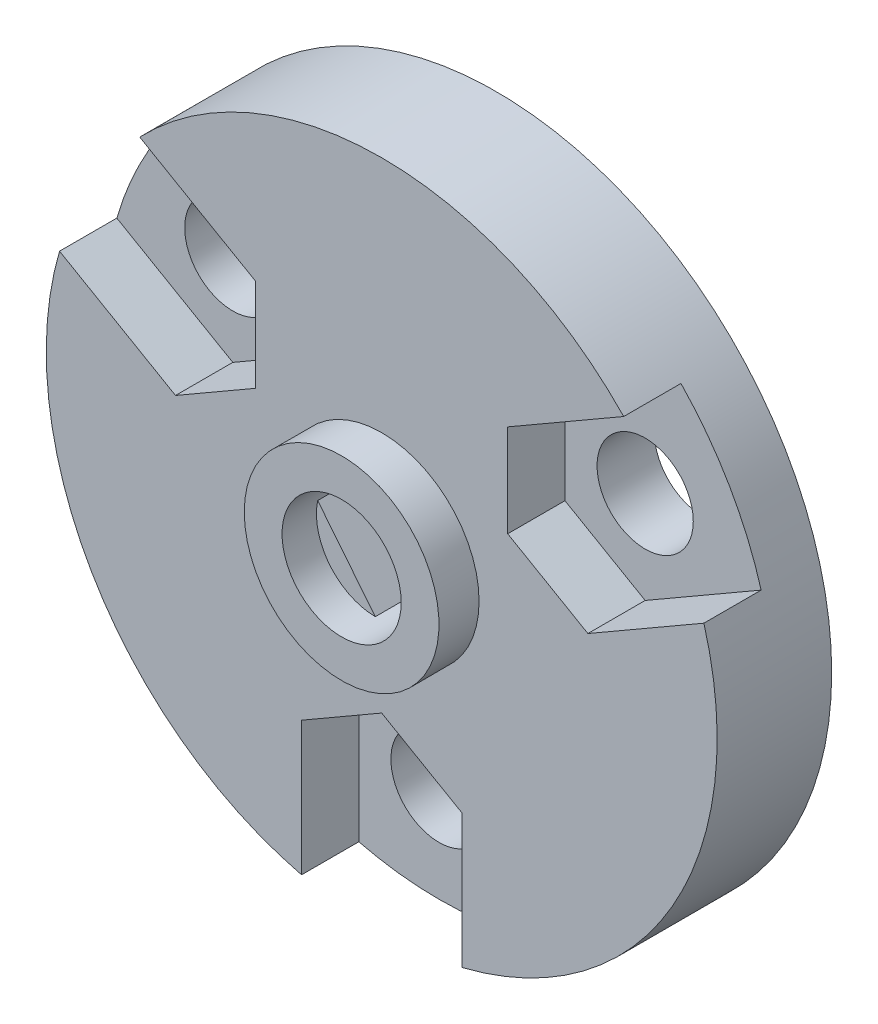
SolidWorks part; units mm, degrees
ref_plane "Front Plane" through (0, 0, 0) normal (0, 0, 1) x (1, 0, 0)
ref_plane "Top Plane" through (0, 0, 0) normal (0, 1, 0) x (1, 0, 0)
ref_plane "Right Plane" through (0, 0, 0) normal (1, 0, 0) x (0, 0, -1)
sketch "Sketch1" plane through (0, 0, 0) normal (0, 0, 1) x (1, 0, 0)
  circle A0 centre (0, 0) radius 14.6423
  circle A1 centre (0, 0) radius 14.6423 construction
extrude "Boss-Extrude1" add sketch "Sketch1" along normal blind 2.5
ref_plane "Plane1" through (0, 0, 2.5) normal (0, 0, 1) x (1, 0, 0)
sketch "Sketch2" plane through (0, 0, 2.5) normal (0, 0, 1) x (1, 0, 0)
  line L0 (9, 9.2376) -> (12.5, 7.2169) construction
  line L1 (12.5, 7.2169) -> (12.5, 3.1754) construction
  line L2 (12.5, 3.1754) -> (9, 1.1547) construction
  line L3 (9, 1.1547) -> (5.5, 3.1754) construction
  line L4 (5.5, 3.1754) -> (5.5, 7.2169) construction
  line L5 (5.5, 7.2169) -> (9, 9.2376) construction
  line L6 (11.125, 1.5155) -> (14.2597, 3.3254) construction
  line L7 (5.5, 7.2169) -> (10.563, 10.14)
  line L8 (5.5, 7.2169) -> (5.5, 3.1754)
  line L9 (5.5, 3.1754) -> (9, 1.1547)
  line L10 (9, 1.1547) -> (14.063, 4.0778)
  line L11 (3.5, -8.3716) -> (3.5, -14.2178)
  line L12 (3.5, -8.3716) -> (0, -6.3509)
  line L13 (0, -6.3509) -> (-3.5, -8.3716)
  line L14 (-3.5, -8.3716) -> (-3.5, -14.2178)
  line L15 (-9, 1.1547) -> (-14.063, 4.0778)
  line L16 (-9, 1.1547) -> (-5.5, 3.1754)
  line L17 (-5.5, 3.1754) -> (-5.5, 7.2169)
  line L18 (-5.5, 7.2169) -> (-10.563, 10.14)
  arc A0 (10.563, 10.14) -> (9.6232, 11.0359) centre (0, 0) ccw
  circle A1 centre (0, 0) radius 14.6423 construction
  circle A2 centre (9, 5.1962) radius 4.0415 construction
  arc A3 (9.6232, 11.0359) -> (-10.563, 10.14) centre (0, 0) ccw
  arc A4 (3.5, -14.2178) -> (14.063, 4.0778) centre (0, 0) ccw
  arc A5 (-14.063, 4.0778) -> (-3.5, -14.2178) centre (0, 0) ccw
  point P38 (0, 0)
  dimension "D1" = 7
  dimension "D2" = 3
extrude "Boss-Extrude2" add sketch "Sketch2" along normal blind 2.5
sketch "Sketch3" plane through (0, 0, 2.5) normal (0, 0, 1) x (1, 0, 0)
  circle A0 centre (-9, 5.1962) radius 2.1
  circle A1 centre (9, 5.1962) radius 2.1
  circle A3 centre (0, -10.3923) radius 2.1
  circle A4 centre (-9, 5.1962) radius 2.1 construction
  circle A5 centre (9, 5.1962) radius 2.1 construction
  circle A7 centre (0, -10.3923) radius 2.1 construction
extrude "Cut-Extrude1" cut sketch "Sketch3" against normal up to next
ref_plane "Plane2" through (0, 0, 5) normal (0, 0, 1) x (1, 0, 0)
sketch "Sketch4" plane through (0, 0, 5) normal (0, 0, 1) x (1, 0, 0)
  circle A0 centre (0, 0) radius 4.25
  circle A1 centre (0, 0) radius 4.25 construction
extrude "Boss-Extrude3" add sketch "Sketch4" along normal offset from surface (1.75 mm away) 0.5
ref_plane "Plane3" through (0, 0, 6.75) normal (0, 0, 1) x (1, 0, 0)
sketch "Sketch5" plane through (0, 0, 6.75) normal (0, 0, 1) x (1, 0, 0)
  circle A0 centre (0, 0) radius 2.6
  circle A1 centre (0, 0) radius 2.6 construction
extrude "Cut-Extrude2" cut sketch "Sketch5" against normal blind 1.5
sketch "Sketch6" plane through (0, 0, 6.75) normal (0, 0, 1) x (1, 0, 0)
  line L0 (2.5442, -0.5358) -> (0.0306, 2.5998)
  line L1 (-0.0306, -2.5998) -> (-2.5442, 0.5358)
  line L2 (2.5442, -0.5358) -> (0.0306, 2.5998) construction
  line L3 (-2.5442, 0.5358) -> (-0.0306, -2.5998) construction
  arc A0 (0.0306, 2.5998) -> (-2.5442, 0.5358) centre (0, 0) ccw
  circle A1 centre (0, 0) radius 2.6 construction
  arc A2 (-0.0306, -2.5998) -> (2.5442, -0.5358) centre (0, 0) ccw
extrude "Cut-Extrude3" cut sketch "Sketch6" against normal through all
